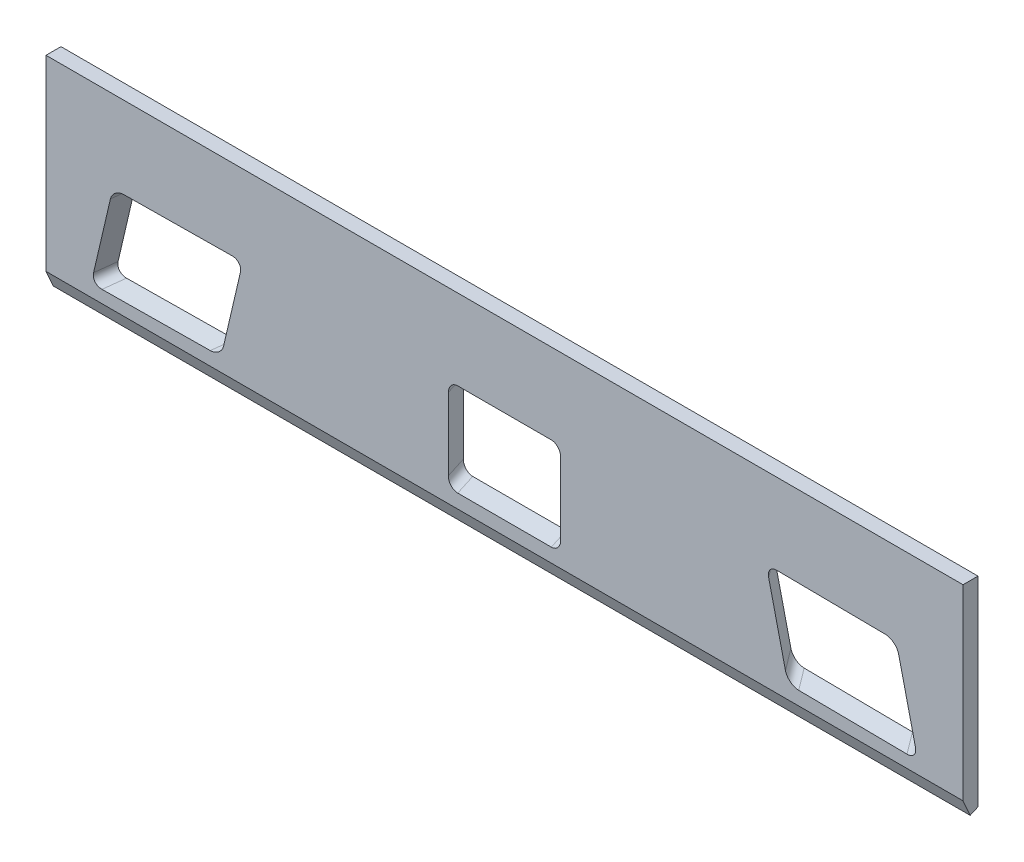
SolidWorks part; units mm, degrees
ref_plane "Alzado" through (0, 0, 0) normal (0, 0, 1) x (1, 0, 0)
ref_plane "Planta" through (0, 0, 0) normal (0, 1, 0) x (1, 0, 0)
ref_plane "Vista lateral" through (0, 0, 0) normal (1, 0, 0) x (0, 0, -1)
sketch "Croquis1" plane through (0, 0, 0) normal (0, 0, 1) x (1, 0, 0)
  line L1 (-49, -10) -> (49, -10)
  line L2 (-49, -10) -> (-49, 10)
  line L3 (-49, 10) -> (49, 10)
  line L4 (49, -10) -> (49, 10)
  line L5 (-49, -10) -> (49, 10) construction
  line L6 (-49, 10) -> (49, -10) construction
  point P0 (0, 0)
  dimension "D1" = 20
  dimension "D2" = 98
extrude "Saliente-Extruir1" add sketch "Croquis1" along normal blind 1.6
sketch "Croquis2" plane through (49, 0, 0) normal (1, 0, 0) x (0, 0, -1)
  line L1 (0, -11.3592) -> (-0.8374, -11.7287)
  line L2 (-0.8374, -11.7287) -> (-1.6, -10)
  line L3 (-1.7492, -10.661) -> (-1.0088, -12.3392) construction
  line L5 (0, -10) -> (0, -11.3592)
  line L9 (0, -10) -> (0, 10)
  line L10 (0, 10) -> (-1.6, 10)
  line L11 (-1.6, 10) -> (-1.6, -10)
  line L12 (-1.6, -10) -> (0, -10)
  line L16 (-1.6, -10) -> (0, -10)
  dimension "D1" = 0
extrude "Saliente-Extruir2" add sketch "Croquis2" against normal blind 98
extrude "Cortar-Extruir1" cut sketch "Croquis3" against normal blind 20 from surface at -8
sketch "Croquis3" plane through (0, -10.2936, -14.5345) normal (0, 0.4211, -0.907) x (-1, 0, 0)
  line L8 (6, 9.4037) -> (6, 16.4037)
  line L9 (5, 17.4037) -> (-5, 17.4037)
  line L10 (-6, 16.4037) -> (-6, 9.4037)
  line L11 (-5, 8.4037) -> (5, 8.4037)
  arc A8 (5, 8.4037) -> (6, 9.4037) centre (5, 9.4037) ccw
  arc A9 (6, 16.4037) -> (5, 17.4037) centre (5, 16.4037) ccw
  arc A10 (-5, 17.4037) -> (-6, 16.4037) centre (-5, 16.4037) ccw
  arc A11 (-6, 9.4037) -> (-5, 8.4037) centre (-5, 9.4037) ccw
extrude "Cortar-Extruir2" cut sketch "Croquis4" against normal blind 20 from surface
sketch "Croquis4" plane through (15.2428, -12.6599, -9.624) normal (-0.4999, 0.367, -0.7845) x (-0.8661, -0.2119, 0.4528)
  line L8 (-8.8281, 9.4895) -> (-8.9056, 16.489)
  line L9 (-9.9167, 17.4779) -> (-19.916, 17.3671)
  line L10 (-20.9049, 16.3561) -> (-20.8274, 9.3565)
  line L11 (-19.8163, 8.3677) -> (-9.817, 8.4784)
  arc A8 (-9.817, 8.4784) -> (-8.8281, 9.4895) centre (-9.828, 9.4784) ccw
  arc A9 (-8.9056, 16.489) -> (-9.9167, 17.4779) centre (-9.9056, 16.4779) ccw
  arc A10 (-19.916, 17.3671) -> (-20.9049, 16.3561) centre (-19.905, 16.3672) ccw
  arc A11 (-20.8274, 9.3565) -> (-19.8163, 8.3677) centre (-19.8274, 9.3676) ccw
mirror "Simetría1" about plane through (0, 0, 0) normal (1, 0, 0) of "Cortar-Extruir2"
